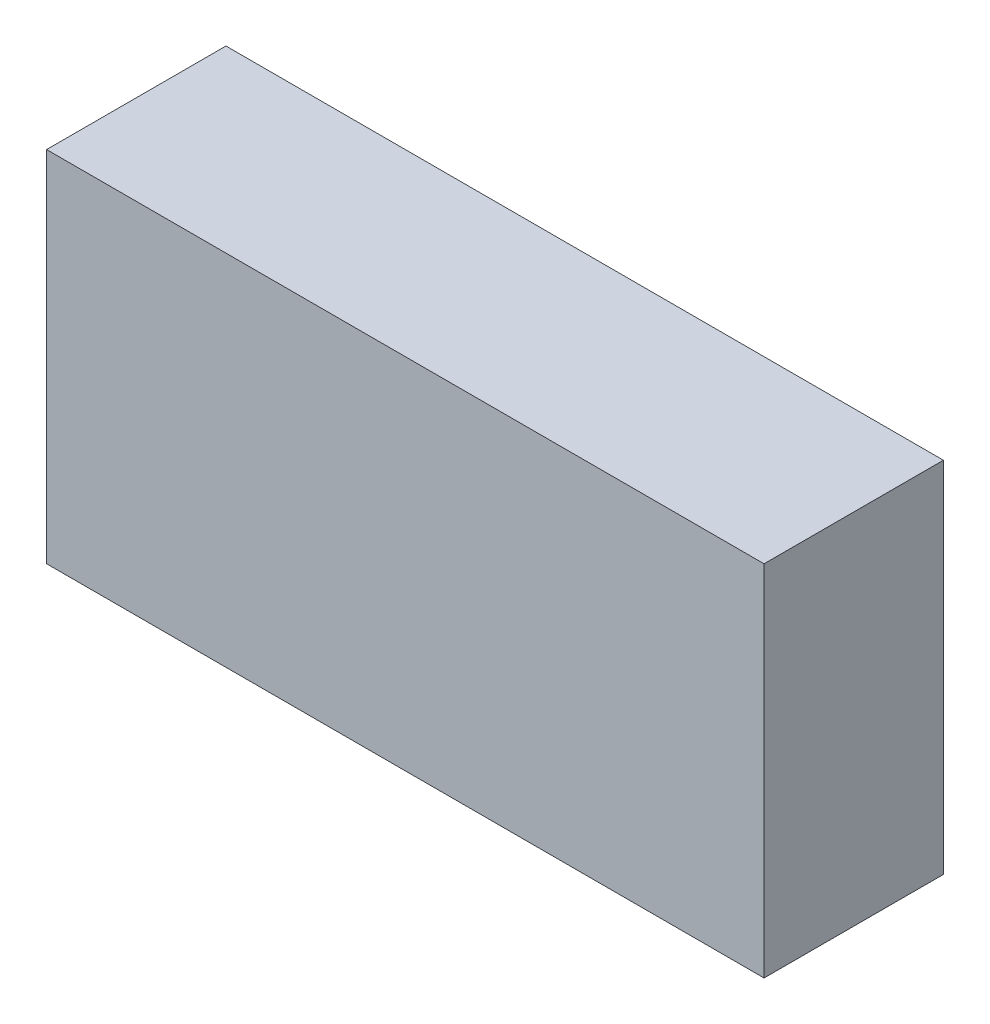
SolidWorks part; units mm, degrees
ref_plane "Front Plane" through (0, 0, 0) normal (0, 0, 1) x (1, 0, 0)
ref_plane "Top Plane" through (0, 0, 0) normal (0, 1, 0) x (1, 0, 0)
ref_plane "Right Plane" through (0, 0, 0) normal (1, 0, 0) x (0, 0, -1)
sketch "Sketch1" plane through (0, 0, 0) normal (0, 0, 1) x (1, 0, 0)
  line L0 (0.825, -0.375) -> (-0.775, -0.375)
  line L1 (-0.775, -0.375) -> (-0.775, 0.425)
  line L2 (-0.775, 0.425) -> (0.825, 0.425)
  line L3 (0.825, 0.425) -> (0.825, -0.375)
extrude "Component_Outline" add sketch "Sketch1" along normal blind 0.4 separate body
sketch3d "3DSketch1"
  line L0 (0, 0, 0) -> (1, 0, 0)
  line L1 (0, 0, 0) -> (0, 1, 0)
  line L2 (0, 0, 0) -> (0, 0, 1)
  point P0 (0, 0, 0)
